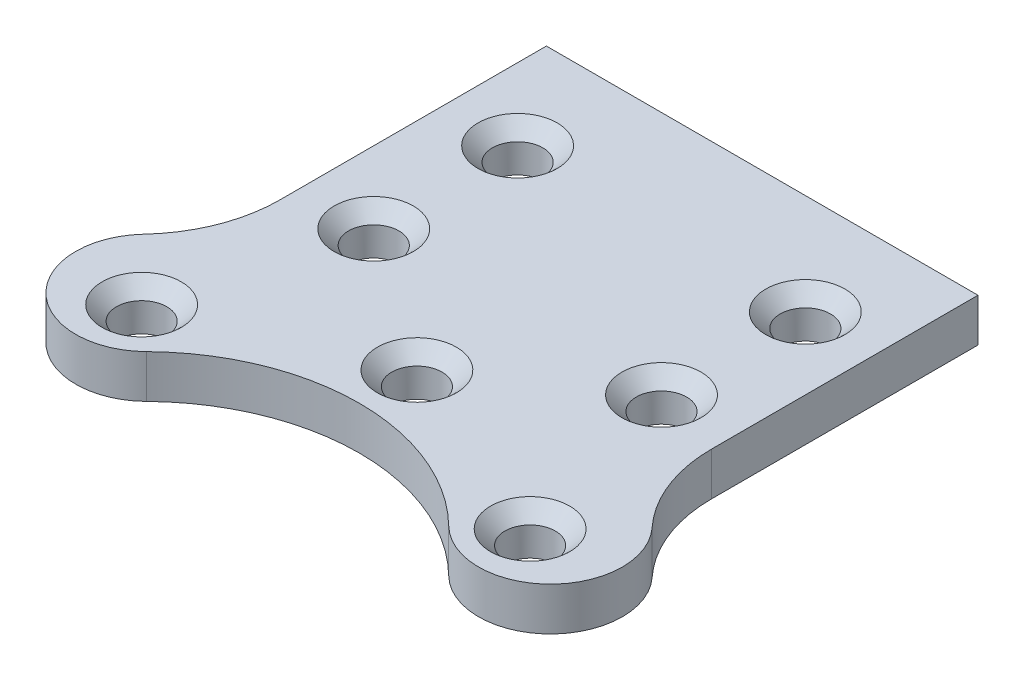
SolidWorks part; units mm, degrees
ref_plane "Front Plane" through (0, 0, 0) normal (0, 0, 1) x (1, 0, 0)
ref_plane "Top Plane" through (0, 0, 0) normal (0, 1, 0) x (1, 0, 0)
ref_plane "Right Plane" through (0, 0, 0) normal (1, 0, 0) x (0, 0, -1)
sketch "Sketch1" plane through (0, 0, 0) normal (0, 1, 0) x (1, 0, 0)
  line L1 (-15, 4.1818) -> (-15, 28)
  line L2 (-15, 28) -> (15, 28)
  line L3 (15, 28) -> (15, 4.1818)
  line L4 (0, 0) -> (0, 41633.4702) construction
  line L5 (-17.356, 4.2829) -> (41616.1142, 4.2829) construction
  line L6 (-33, 28) -> (33, 28) construction
  arc A0 (10.5, -4.2879) -> (15, 4.1818) centre (14, -0.7171) ccw
  arc A1 (-10.5, -4.2879) -> (-15, 4.1818) centre (-14, -0.7171) cw
  arc A2 (-10.5, -4.2879) -> (10.5, -4.2879) centre (0, -15) cw
  dimension "D2" = 5
  dimension "D4" = 15
  dimension "D1" = 30
  dimension "D3" = 28
extrude "Boss-Extrude1" add sketch "Sketch1" along normal blind 3
fillet "Fillet1" radius 10 2 edges at (15, 1.5, -4.1818) (-15, 1.5, -4.1818)
sketch "Sketch2" plane through (0, 3, 0) normal (0, 1, 0) x (1, 0, 0)
  line L0 (0, 0) -> (0, 50000) construction
  line L1 (-10.6795, 21) -> (49989.3205, 21) construction
  line L2 (-10, 11) -> (49990, 11) construction
  line L3 (-10, 22.4177) -> (-10, -49977.5823) construction
  line L4 (10, 22.4177) -> (10, -49977.5823) construction
  circle A0 centre (0, 4) radius 1.75
  circle A2 centre (13.5, -1.6303) radius 1.75
  circle A4 centre (-13.5, -1.6303) radius 1.75
  circle A5 centre (0, -15) radius 19 construction
  arc A6 (10.5, -4.2879) -> (-10.5, -4.2879) centre (0, -15) ccw construction
  circle A7 centre (-10, 11) radius 1.75
  circle A8 centre (-10, 21) radius 1.75
  circle A9 centre (10, 21) radius 1.75
  circle A10 centre (10, 11) radius 1.75
  point P18 (0, 0)
  dimension "D1" = 38
  dimension "D2" = 3.5
  dimension "D3" = 27
  dimension "D5" = 20
  dimension "D6" = 10
  dimension "D7" = 7
extrude "Cut-Extrude1" cut sketch "Sketch2" against normal through all
chamfer "Chamfer1" distance 1 angle 45 7 edges at (13.5, 3, 3.3803) (-13.5, 3, 3.3803) (-10, 3, -9.25) (0, 3, -2.25) (10, 3, -9.25) (10, 3, -19.25) (-10, 3, -19.25)
